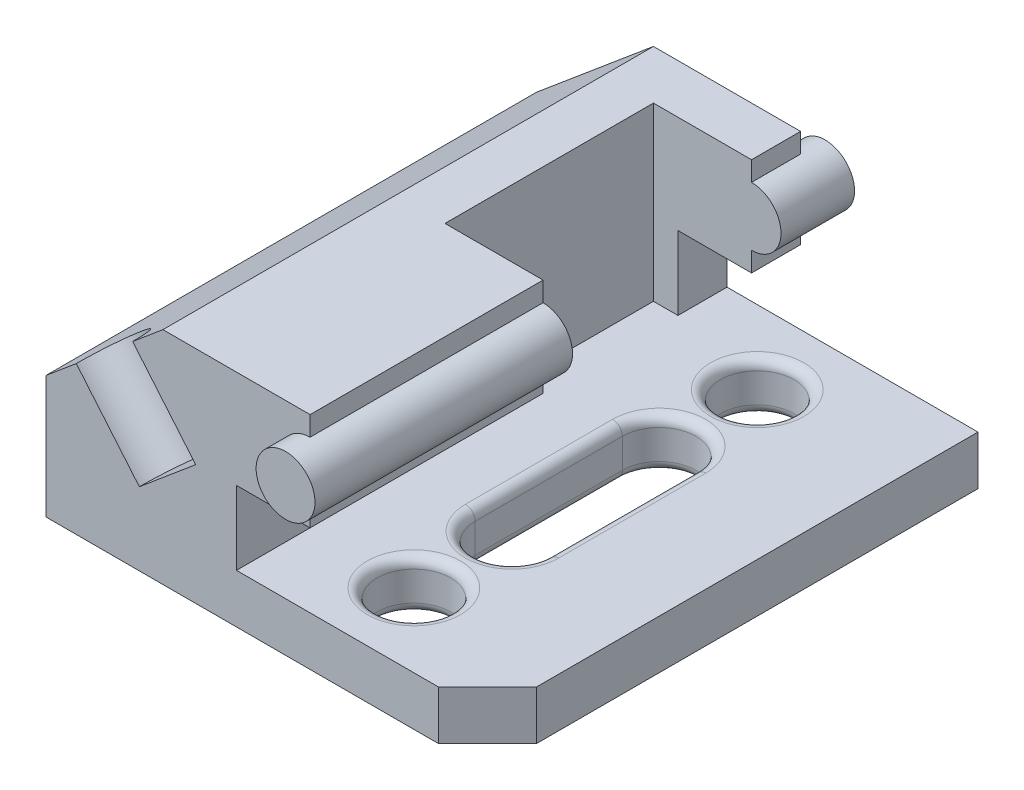
SolidWorks part; units mm, degrees
material "1060 Alloy"
ref_plane "Front Plane" through (0, 0, 0) normal (0, 0, 1) x (1, 0, 0)
ref_plane "Top Plane" through (0, 0, 0) normal (0, 1, 0) x (1, 0, 0)
ref_plane "Right Plane" through (0, 0, 0) normal (1, 0, 0) x (0, 0, -1)
sketch "Sketch1" plane through (0, 0, 0) normal (0, 1, 0) x (1, 0, 0)
  line L1 (-90, -100) -> (-10, -100)
  line L2 (-90, -100) -> (-90, 0)
  line L3 (-90, 0) -> (0, 0)
  line L4 (0, -90) -> (0, 0)
  line L5 (0, -90) -> (-10, -100)
  point P3 (0, 0)
  dimension "D1" = 90
  dimension "D2" = 100
  dimension "D3" = 10
  dimension "D4" = 45
extrude "Boss-Extrude1" add sketch "Sketch1" against normal blind 10
sketch "Sketch2" plane through (0, 0, 0) normal (0, 1, 0) x (1, 0, 0)
  line L0 (-30, -65) -> (-30, -35) construction
  line L1 (-37.5, -65) -> (-37.5, -35)
  line L2 (-22.5, -65) -> (-22.5, -35)
  line L3 (0, -90) -> (0, 0) construction
  line L4 (0, 0) -> (-90, 0) construction
  line L5 (-90, -100) -> (-10, -100) construction
  circle A0 centre (-30, -15) radius 7.5
  circle A1 centre (-30, -85) radius 7.5
  arc A2 (-37.5, -65) -> (-22.5, -65) centre (-30, -65) ccw
  arc A3 (-22.5, -35) -> (-37.5, -35) centre (-30, -35) ccw
  point P6 (-30, -50)
  dimension "D7" = 15
  dimension "D8" = 15
  dimension "D1" = 15
  dimension "D2" = 30
  dimension "D3" = 30
  dimension "D4" = 15
  dimension "D5" = 15
  dimension "D6" = 20
extrude "Cut-Extrude1" cut sketch "Sketch2" against normal through all
fillet "Fillet1" radius 2 12 edges at (-30, -10, 27.5) (-22.5, -10, 50) (-30, -10, 72.5) (-30, 0, 27.5) (-22.5, 0, 50) (-30, 0, 72.5) (-30, -10, 22.5) (-30, -10, 92.5) (-37.5, -10, 50) (-30, 0, 92.5) (-30, 0, 22.5) (-37.5, 0, 50)
sketch "Sketch3" plane through (0, 0, 100) normal (0, 0, 1) x (1, 0, 0)
  line L0 (-90, -10) -> (-90, 15)
  line L1 (-90, 15) -> (-66.1649, 35)
  line L2 (-66.1649, 35) -> (-36.1649, 35)
  line L3 (-36.1649, 35) -> (-36.1649, 15)
  line L4 (-36.1649, 15) -> (-51.1649, 15)
  line L5 (-51.1649, 15) -> (-51.1649, -10)
  line L6 (-90, -10) -> (-10, -10) construction
  line L7 (-51.1649, -10) -> (-90, -10)
  line L8 (-90, 0) -> (-10, 0) construction
  dimension "D1" = 30
  dimension "D2" = 15
  dimension "D3" = 25
  dimension "D4" = 20
  dimension "D5" = 50
  dimension "D6" = 15
extrude "Boss-Extrude2" add sketch "Sketch3" against normal through all
sketch "Sketch4" plane through (0, 0, 100) normal (0, 0, 1) x (1, 0, 0)
  line L0 (-36.1649, 15) -> (-36.1649, 35) construction
  circle A0 centre (-36.1649, 25) radius 6
  dimension "D1" = 12
extrude "Boss-Extrude3" add sketch "Sketch4" along normal blind 5 and the other way blind 105
sketch "Sketch5" plane through (0, 35, 0) normal (0, 1, 0) x (1, 0, 0)
  line L0 (-30.1649, -105) -> (-30.1649, 5) construction
  line L1 (-56.1649, -52.5) -> (-30.1649, -52.5)
  line L2 (-56.1649, -52.5) -> (-56.1649, -10)
  line L3 (-56.1649, -10) -> (-30.1649, -10)
  line L4 (-30.1649, -52.5) -> (-30.1649, -10)
  line L5 (-66.1649, 0) -> (-66.1649, -100) construction
  line L6 (-36.1649, 0) -> (-66.1649, 0) construction
  dimension "D1" = 10
  dimension "D2" = 10
  dimension "D3" = 42.5
extrude "Cut-Extrude2" cut sketch "Sketch5" against normal blind 35 and the other way through all
sketch "Sketch6" plane through (-44.5719, 53.1187, 0) normal (-0.6428, 0.766, 0) x (0.766, 0.6428, 0)
  line L0 (-28.1877, -100) -> (-59.3022, -100) construction
  circle A0 centre (-43.7449, -100) radius 7.5
  point P4 (-43.7449, -100)
  dimension "D1" = 15
extrude "Cut-Extrude3" cut sketch "Sketch6" against normal blind 20
